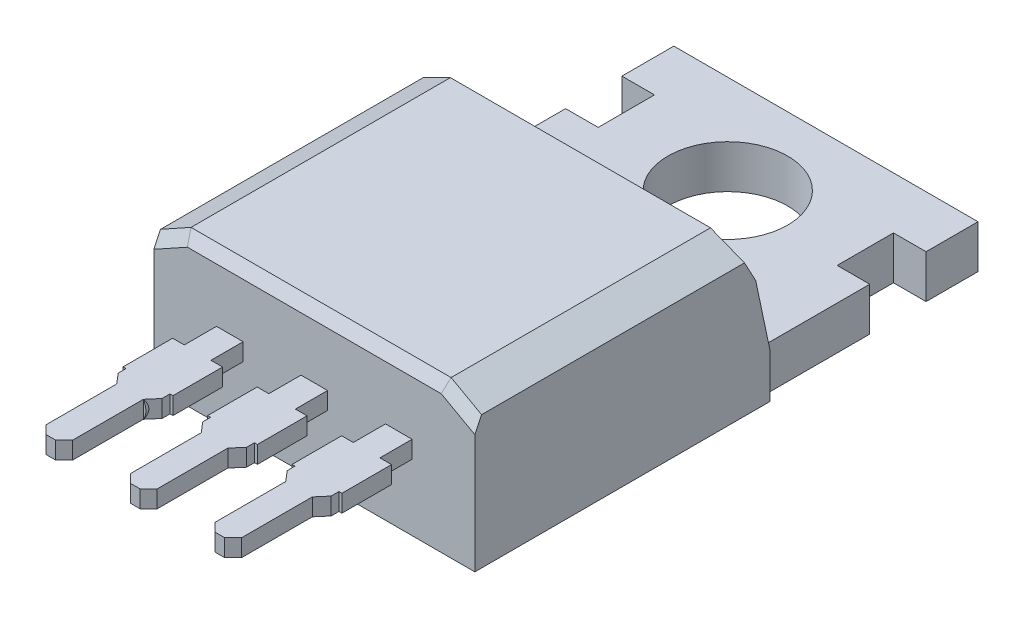
SolidWorks part; units mm, degrees
ref_plane "Front Plane" through (0, 0, 0) normal (0, 0, 1) x (1, 0, 0)
ref_plane "Top Plane" through (0, 0, 0) normal (0, 1, 0) x (1, 0, 0)
ref_plane "Right Plane" through (0, 0, 0) normal (1, 0, 0) x (0, 0, -1)
sketch "Sketch1" plane through (0, 0, 0) normal (0, 1, 0) x (1, 0, 0)
  line L0 (4.826, -1.0795) -> (-4.826, -1.0795)
  line L1 (4.826, -7.3025) -> (-4.826, -7.3025)
  line L2 (4.826, -7.3025) -> (4.826, 8.2138)
  line L3 (4.826, 7.3025) -> (-4.826, 7.3025)
  line L4 (-4.826, -7.3025) -> (-4.826, 8.2138)
  line L5 (4.826, -7.3025) -> (-4.826, 7.3025) construction
  line L6 (4.826, 7.3025) -> (-4.826, -7.3025) construction
  line L7 (4.826, -1.0795) -> (-4.826, -1.0795)
  line L8 (3.7898, 8.9789) -> (-3.7898, 8.9789)
  line L9 (-4.826, 8.2138) -> (-3.7898, 8.9789)
  line L10 (0, 7.3025) -> (0, 12.7866) construction
  line L11 (4.826, 8.2138) -> (3.7898, 8.9789)
  line L12 (4.826, 8.9789) -> (-4.826, 8.9789) construction
  point P0 (0, 0)
  dimension "D1" = 9.652
  dimension "D2" = 14.605
  dimension "D3" = 8.382
  dimension "D4" = 8.382
  dimension "D5" = 1.6764
sketch "Sketch2" plane through (0, 0, 0) normal (1, 0, 0) x (0, 0, -1)
  line L0 (14.3005, 0) -> (-1.0795, 0)
  line L1 (7.3025, 0) -> (12.7866, 0) construction
  line L2 (7.8005, 1.3) -> (7.124, 4.5)
  line L3 (7.124, 4.5) -> (-1.0795, 4.5)
  line L4 (-1.0795, 4.5) -> (-1.0795, 0)
  line L5 (14.3005, 1.3) -> (14.3005, 0)
  line L6 (14.3005, 1.3) -> (7.8005, 1.3)
  line L7 (14.3005, 1.3) -> (-7.3025, 1.3) construction
  line L8 (14.3005, 0) -> (-7.3025, 0) construction
  dimension "D1" = 4.5
  dimension "D3" = 6.5
  dimension "D2" = 15.38
extrude "Extrude1" add sketch "Sketch2" against normal up to vertex (4.826 mm away) and the other way up to vertex (4.826 mm away) up to point (-4.826, 0, 1.0795) other way up to point (4.826, 0, 1.0795)
sketch "Sketch10" plane through (0, 1.3, 0) normal (0, 1, 0) x (1, 0, 0)
  line L0 (0, 7.8005) -> (0, 16.6747) construction
  line L1 (-4.826, 7.8005) -> (4.826, 7.8005) construction
  line L2 (-4.826, 14.3005) -> (4.826, 14.3005) construction
  line L3 (-4.826, 14.3005) -> (-4.826, 7.8005) construction
  line L4 (-4.826, 12.7393) -> (-3.5922, 12.7393)
  line L5 (-4.826, 12.7393) -> (-4.826, 11.0462)
  line L6 (-4.826, 11.0462) -> (-3.5922, 11.0462)
  line L7 (-3.5922, 12.7393) -> (-3.5922, 11.0462)
  line L8 (3.5922, 12.7393) -> (3.5922, 11.0462)
  line L9 (4.826, 11.0462) -> (3.5922, 11.0462)
  line L10 (4.826, 12.7393) -> (4.826, 11.0462)
  line L11 (4.826, 12.7393) -> (3.5922, 12.7393)
  circle A0 centre (0, 11.3505) radius 1.8
  dimension "D1" = 3.6
  dimension "D2" = 2.95
extrude "Extrude5" cut sketch "Sketch10" against normal through all
sketch "Sketch6" plane through (0, 0, 1.0795) normal (0, 0, 1) x (1, 0, 0)
  line L0 (0, 4.5) -> (0, 0) construction
  line L1 (-4.826, 4.5) -> (4.826, 4.5) construction
  line L2 (-2.54, 4.5) -> (-2.54, 0) construction
  line L3 (2.54, 4.5) -> (2.54, 0) construction
  line L4 (-4.826, 2.25) -> (4.826, 2.25) construction
  line L5 (-4.826, 4.5) -> (-4.826, 0) construction
  line L6 (4.826, 4.5) -> (4.826, 0) construction
  line L7 (2.14, 2.51) -> (2.94, 2.51)
  line L8 (-2.94, 2.51) -> (-2.14, 2.51)
  line L9 (-2.94, 2.51) -> (-2.94, 1.99)
  line L10 (-2.94, 1.99) -> (-2.14, 1.99)
  line L11 (-2.14, 2.51) -> (-2.14, 1.99)
  line L12 (-2.94, 2.51) -> (-2.14, 1.99) construction
  line L13 (-2.94, 1.99) -> (-2.14, 2.51) construction
  line L14 (2.14, 2.51) -> (2.14, 1.99)
  line L15 (2.14, 1.99) -> (2.94, 1.99)
  line L16 (2.94, 2.51) -> (2.94, 1.99)
  line L17 (2.14, 2.51) -> (2.94, 1.99) construction
  line L18 (2.14, 1.99) -> (2.94, 2.51) construction
  line L19 (-0.4, 2.51) -> (0.4, 2.51)
  line L20 (-0.4, 2.51) -> (-0.4, 1.99)
  line L21 (-0.4, 1.99) -> (0.4, 1.99)
  line L22 (0.4, 2.51) -> (0.4, 1.99)
  line L23 (-0.4, 2.51) -> (0.4, 1.99) construction
  line L24 (-0.4, 1.99) -> (0.4, 2.51) construction
  point P15 (-2.54, 2.25)
  point P21 (2.54, 2.25)
  point P26 (0, 2.25)
  dimension "D3" = 0.8
  dimension "D4" = 0.52
  dimension "D5" = 0.8
  dimension "D6" = 0.8
  dimension "D1" = 2.54
  dimension "D2" = 2.54
extrude "Extrude6" add sketch "Sketch6" along normal blind 5.38
sketch "Sketch11" plane through (0, 2.51, 0) normal (0, 1, 0) x (1, 0, 0)
  line L0 (-2.94, -3.7695) -> (-2.14, -3.7695) construction
  line L1 (-2.94, -6.4595) -> (-2.94, -1.0795) construction
  line L2 (-2.14, -6.4595) -> (-2.14, -1.0795) construction
  line L3 (-2.54, -3.7695) -> (-2.54, -2.5379) construction
  line L4 (-4.826, -1.0795) -> (4.826, -1.0795) construction
  line L5 (-3.29, -2.0475) -> (-1.79, -2.0475)
  line L6 (-3.29, -2.0475) -> (-3.29, -3.5395)
  line L7 (-2.94, -4.0795) -> (-2.14, -4.0795)
  line L8 (-1.8796, -3.7747) -> (-1.8796, -3.5395)
  line L9 (-3.29, -2.0475) -> (-1.869, -4.1434) construction
  line L10 (-3.1272, -4.0199) -> (-1.79, -2.0475) construction
  line L11 (-3.29, -3.5395) -> (-3.2004, -3.5395)
  line L12 (-0.75, -2.0475) -> (0.75, -2.0475)
  line L13 (-2.14, -4.0795) -> (-1.8796, -3.7747)
  line L14 (-2.94, -4.0795) -> (-3.2004, -3.7747)
  line L15 (-3.2004, -3.7747) -> (-3.2004, -3.5395)
  line L16 (-1.79, -3.5395) -> (-1.8796, -3.5395)
  line L17 (-1.79, -2.0475) -> (-1.79, -3.5395)
  line L18 (-0.75, -2.0475) -> (-0.75, -3.5395)
  line L19 (-0.4, -4.0795) -> (0.4, -4.0795)
  line L20 (0.6604, -3.7747) -> (0.6604, -3.5395)
  line L21 (-0.75, -3.5395) -> (-0.6604, -3.5395)
  line L22 (0.4, -4.0795) -> (0.6604, -3.7747)
  line L23 (-0.4, -4.0795) -> (-0.6604, -3.7747)
  line L24 (-0.6604, -3.7747) -> (-0.6604, -3.5395)
  line L25 (0.75, -3.5395) -> (0.6604, -3.5395)
  line L26 (0.75, -2.0475) -> (0.75, -3.5395)
  line L27 (-0.75, -2.0475) -> (0.671, -4.1434) construction
  line L28 (-0.5872, -4.0199) -> (0.75, -2.0475) construction
  line L29 (1.79, -2.0475) -> (3.29, -2.0475)
  line L30 (1.79, -2.0475) -> (1.79, -3.5395)
  line L31 (2.14, -4.0795) -> (2.94, -4.0795)
  line L32 (3.2004, -3.7747) -> (3.2004, -3.5395)
  line L33 (1.79, -3.5395) -> (1.8796, -3.5395)
  line L34 (2.94, -4.0795) -> (3.2004, -3.7747)
  line L35 (2.14, -4.0795) -> (1.8796, -3.7747)
  line L36 (1.8796, -3.7747) -> (1.8796, -3.5395)
  line L37 (3.29, -3.5395) -> (3.2004, -3.5395)
  line L38 (3.29, -2.0475) -> (3.29, -3.5395)
  line L39 (1.79, -2.0475) -> (3.211, -4.1434) construction
  line L40 (1.9528, -4.0199) -> (3.29, -2.0475) construction
  point P8 (-2.54, -3.1537)
  point P15 (0, -3.1537)
  point P25 (-2.54, -4.0795)
  point P27 (-2.54, -2.0475)
  point P38 (0, -4.0795)
  point P40 (0, -2.0475)
  point P41 (2.54, -3.1537)
  point P53 (2.54, -4.0795)
  point P55 (2.54, -2.0475)
  dimension "D1" = 2.032
  dimension "D2" = 3
  dimension "D3" = 2.46
  dimension "D5" = 1.5
  dimension "D6" = 0.3048
  dimension "D4" = 1.3208
extrude "Extrude7" add sketch "Sketch11" against normal up to vertex
chamfer "Chamfer1" distance 0.254 angle 45 6 edges at (2.94, 2.25, 6.4595) (2.14, 2.25, 6.4595) (0.4, 2.25, 6.4595) (-0.4, 2.25, 6.4595) (-2.14, 2.25, 6.4595) (-2.94, 2.25, 6.4595)
sketch "Sketch12" plane through (-4.826, 0, 0) normal (-1, 0, 0) x (0, 0, 1)
  line L0 (1.0795, 0) -> (-11.0462, 0) construction
  line L1 (-15.1802, 2.7361) -> (-7.8005, 2.7361)
  line L2 (-15.1802, 2.7361) -> (-15.1802, 0)
  line L3 (-15.1802, 0) -> (-7.8005, 0)
  line L4 (-7.8005, 2.7361) -> (-7.8005, 0)
extrude "Extrude8" cut sketch "Sketch12" against normal blind 0.254
sketch "Sketch13" plane through (4.826, 0, 0) normal (1, 0, 0) x (0, 0, -1)
  line L4 (15.1802, 2.7361) -> (7.8005, 2.7361)
  line L5 (7.8005, 2.7361) -> (7.8005, 0)
  line L6 (7.8005, 0) -> (15.1802, 0)
  line L7 (15.1802, 0) -> (15.1802, 2.7361)
  line L8 (15.1802, 2.7361) -> (7.8005, 2.7361)
  line L9 (7.8005, 2.7361) -> (7.8005, 0)
  line L10 (7.8005, 0) -> (15.1802, 0)
  line L11 (15.1802, 0) -> (15.1802, 2.7361)
  dimension "D1" = 0
extrude "Extrude9" cut sketch "Sketch13" against normal blind 0.254
chamfer "Chamfer2" distance 0.508 angle 61 2 edges at (4.826, 4.5, -3.0223) (-4.826, 4.5, -3.0223)
chamfer "Chamfer3" distance 0.2032 angle 61 6 edges at (4.3678, 4.246, 1.0795) (0, 4.5, 1.0795) (-4.3678, 4.246, 1.0795) (4.3678, 4.246, -7.1777) (0, 4.5, -7.124) (-4.3678, 4.246, -7.1777)
ref_plane "Plane1" through (0, 0, 4.0795) normal (0, 0, 1) x (1, 0, 0)
sketch "Sketch15" plane through (0, 0, 4.0795) normal (0, 0, 1) x (1, 0, 0)
  line L0 (-2.14, 2.51) -> (-2.94, 2.51) construction
  line L1 (-2.14, 2.51) -> (-2.94, 2.51)
  line L2 (-2.94, 1.99) -> (-2.14, 1.99) construction
  line L3 (-2.94, 1.99) -> (-2.14, 1.99)
  arc A0 (-2.14, 1.99) -> (-2.14, 2.51) centre (-2.54, 2.25) ccw
  arc A1 (-2.94, 2.51) -> (-2.94, 1.99) centre (-2.54, 2.25) ccw
extrude "Extrude10" add sketch "Sketch15" against normal blind 1.016
